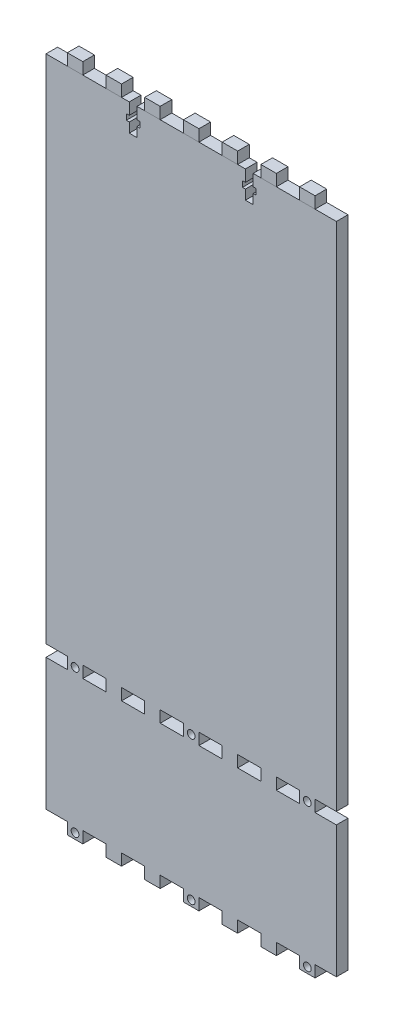
SolidWorks part; units mm, degrees
ref_plane "Plan de face" through (0, 0, 0) normal (0, 0, 1) x (1, 0, 0)
ref_plane "Plan de dessus" through (0, 0, 0) normal (0, 1, 0) x (1, 0, 0)
ref_plane "Plan de droite" through (0, 0, 0) normal (1, 0, 0) x (0, 0, -1)
sketch "Esquisse1" plane through (0, 0, 0) normal (0, 0, 1) x (1, 0, 0)
  line L0 (-166.0227, 1.3653) -> (-16.0227, 1.3653)
  line L1 (-166.0227, 75.3653) -> (-16.0227, 75.3653)
  line L2 (-166.0227, 75.3653) -> (-166.0227, 7.3653)
  line L3 (-166.0227, 7.3653) -> (-16.0227, 7.3653)
  line L4 (-16.0227, 75.3653) -> (-16.0227, 7.3653)
  line L5 (-166.0227, 7.3653) -> (-155.0227, 7.3653)
  line L6 (-166.0227, 7.3653) -> (-166.0227, 1.3653)
  line L7 (-166.0227, 1.3653) -> (-155.0227, 1.3653)
  line L8 (-155.0227, 7.3653) -> (-155.0227, 1.3653)
  line L9 (-155.0227, 1.3653) -> (-147.0227, 1.3653)
  line L10 (-155.0227, 1.3653) -> (-155.0227, 7.3653)
  line L11 (-155.0227, 7.3653) -> (-147.0227, 7.3653)
  line L12 (-147.0227, 1.3653) -> (-147.0227, 7.3653)
  line L13 (-127.0227, 1.3653) -> (-127.0227, 7.3653)
  line L14 (-135.0227, 1.3653) -> (-127.0227, 1.3653)
  line L15 (-135.0227, 7.3653) -> (-135.0227, 1.3653)
  line L16 (-146.0227, 1.3653) -> (-135.0227, 1.3653)
  line L17 (-166.0227, 41.3653) -> (-16.0227, 41.3653) construction
  line L18 (-107.0227, 1.3653) -> (-107.0227, 7.3653)
  line L19 (-115.0227, 1.3653) -> (-107.0227, 1.3653)
  line L20 (-115.0227, 7.3653) -> (-115.0227, 1.3653)
  line L21 (-126.0227, 1.3653) -> (-115.0227, 1.3653)
  line L22 (-46.0227, 81.3653) -> (-35.0227, 81.3653)
  line L23 (-87.0227, 1.3653) -> (-87.0227, 7.3653)
  line L24 (-95.0227, 1.3653) -> (-87.0227, 1.3653)
  line L25 (-95.0227, 7.3653) -> (-95.0227, 1.3653)
  line L26 (-106.0227, 1.3653) -> (-95.0227, 1.3653)
  line L27 (-35.0227, 75.3653) -> (-35.0227, 81.3653)
  line L28 (-67.0227, 1.3653) -> (-67.0227, 7.3653)
  line L29 (-75.0227, 1.3653) -> (-67.0227, 1.3653)
  line L30 (-75.0227, 7.3653) -> (-75.0227, 1.3653)
  line L31 (-86.0227, 1.3653) -> (-75.0227, 1.3653)
  line L32 (-35.0227, 81.3653) -> (-27.0227, 81.3653)
  line L33 (-47.0227, 1.3653) -> (-47.0227, 7.3653)
  line L34 (-55.0227, 1.3653) -> (-47.0227, 1.3653)
  line L35 (-55.0227, 7.3653) -> (-55.0227, 1.3653)
  line L36 (-66.0227, 1.3653) -> (-55.0227, 1.3653)
  line L37 (-27.0227, 81.3653) -> (-27.0227, 75.3653)
  line L38 (-27.0227, 1.3653) -> (-27.0227, 7.3653)
  line L39 (-35.0227, 1.3653) -> (-27.0227, 1.3653)
  line L40 (-35.0227, 7.3653) -> (-35.0227, 1.3653)
  line L41 (-46.0227, 1.3653) -> (-35.0227, 1.3653)
  line L42 (-66.0227, 81.3653) -> (-55.0227, 81.3653)
  line L43 (-55.0227, 75.3653) -> (-55.0227, 81.3653)
  line L44 (-55.0227, 81.3653) -> (-47.0227, 81.3653)
  line L45 (-47.0227, 81.3653) -> (-47.0227, 75.3653)
  line L46 (-86.0227, 81.3653) -> (-75.0227, 81.3653)
  line L47 (-75.0227, 75.3653) -> (-75.0227, 81.3653)
  line L48 (-75.0227, 81.3653) -> (-67.0227, 81.3653)
  line L49 (-67.0227, 81.3653) -> (-67.0227, 75.3653)
  line L50 (-106.0227, 81.3653) -> (-95.0227, 81.3653)
  line L51 (-95.0227, 75.3653) -> (-95.0227, 81.3653)
  line L52 (-95.0227, 81.3653) -> (-87.0227, 81.3653)
  line L53 (-87.0227, 81.3653) -> (-87.0227, 75.3653)
  line L54 (-126.0227, 81.3653) -> (-115.0227, 81.3653)
  line L55 (-115.0227, 75.3653) -> (-115.0227, 81.3653)
  line L56 (-115.0227, 81.3653) -> (-107.0227, 81.3653)
  line L57 (-107.0227, 81.3653) -> (-107.0227, 75.3653)
  line L58 (-146.0227, 81.3653) -> (-135.0227, 81.3653)
  line L59 (-135.0227, 75.3653) -> (-135.0227, 81.3653)
  line L60 (-135.0227, 81.3653) -> (-127.0227, 81.3653)
  line L61 (-127.0227, 81.3653) -> (-127.0227, 75.3653)
  line L62 (-147.0227, 81.3653) -> (-147.0227, 75.3653)
  line L63 (-155.0227, 75.3653) -> (-147.0227, 75.3653)
  line L64 (-155.0227, 81.3653) -> (-155.0227, 75.3653)
  line L65 (-155.0227, 81.3653) -> (-147.0227, 81.3653)
  line L66 (-155.0227, 75.3653) -> (-155.0227, 81.3653)
  line L67 (-166.0227, 81.3653) -> (-155.0227, 81.3653)
  line L68 (-166.0227, 75.3653) -> (-166.0227, 81.3653)
  line L69 (-166.0227, 75.3653) -> (-155.0227, 75.3653)
  line L70 (-166.0227, 75.3653) -> (-16.0227, 75.3653)
  line L71 (-166.0227, 81.3653) -> (-16.0227, 81.3653)
  line L72 (-16.0227, 81.3653) -> (-16.0227, 1.3653)
  dimension "D1" = 68
  dimension "D2" = 150
  dimension "D3" = 6
  dimension "D4" = 11
  dimension "D5" = 8
extrude "Boss.-Extru.1" add sketch "Esquisse1" along normal blind 6 contours L65 L64 L1 L62 | L61 L60 L59 L1 | L57 L56 L55 L1 | L53 L52 L51 L1 | L49 L48 L47 L1 | L45 L44 L43 L1 | L37 L32 L27 L1 | L3 L40 L0 L38 | L3 L35 L0 L33 | L3 L30 L0 L28 | L3 L25 L0 L23 | L3 L20 L0 L18 | L3 L15 L0 L13 | L0 L12 L3 L8 | L17 L2 L3 L72 | L2 L17 L4 L1
sketch "Esquisse2" plane through (0, 0, 6) normal (0, 0, 1) x (1, 0, 0)
  line L0 (-16.0227, 81.3653) -> (-166.0227, 81.3653)
  line L1 (-16.0227, 81.3653) -> (-16.0227, 345.3653)
  line L2 (-16.0227, 345.3653) -> (-166.0227, 345.3653)
  line L3 (-166.0227, 81.3653) -> (-166.0227, 345.3653)
  line L4 (-135.0227, 81.3653) -> (-127.0227, 81.3653) construction
  line L5 (-166.0227, 75.3653) -> (-166.0227, 7.3653) construction
  dimension "D1" = 264
  dimension "D2" = 150
extrude "Boss.-Extru.2" add sketch "Esquisse2" against normal blind 6
sketch "Esquisse3" plane through (0, 0, 6) normal (0, 0, 1) x (1, 0, 0)
  line L0 (-155.0227, 345.3653) -> (-147.0227, 345.3653)
  line L1 (-155.0227, 345.3653) -> (-155.0227, 351.3653)
  line L2 (-155.0227, 351.3653) -> (-147.0227, 351.3653)
  line L3 (-147.0227, 345.3653) -> (-147.0227, 351.3653)
  line L4 (-135.0227, 345.3653) -> (-127.0227, 345.3653)
  line L5 (-135.0227, 345.3653) -> (-135.0227, 351.3653)
  line L6 (-135.0227, 351.3653) -> (-127.0227, 351.3653)
  line L7 (-127.0227, 345.3653) -> (-127.0227, 351.3653)
  line L8 (-115.0598, 345.3653) -> (-107.0598, 345.3653)
  line L9 (-115.0598, 345.3653) -> (-115.0598, 351.3653)
  line L10 (-115.0598, 351.3653) -> (-107.0598, 351.3653)
  line L11 (-107.0598, 345.3653) -> (-107.0598, 351.3653)
  line L12 (-95.0227, 345.3653) -> (-87.0227, 345.3653)
  line L13 (-95.0227, 345.3653) -> (-95.0227, 351.3653)
  line L14 (-95.0227, 351.3653) -> (-87.0227, 351.3653)
  line L15 (-87.0227, 345.3653) -> (-87.0227, 351.3653)
  line L16 (-75.0227, 345.3653) -> (-67.0227, 345.3653)
  line L17 (-75.0227, 345.3653) -> (-75.0227, 351.3653)
  line L18 (-75.0227, 351.3653) -> (-67.0227, 351.3653)
  line L19 (-67.0227, 345.3653) -> (-67.0227, 351.3653)
  line L20 (-55.0227, 345.3653) -> (-47.0227, 345.3653)
  line L21 (-55.0227, 345.3653) -> (-55.0227, 351.3653)
  line L22 (-55.0227, 351.3653) -> (-47.0227, 351.3653)
  line L23 (-47.0227, 345.3653) -> (-47.0227, 351.3653)
  line L24 (-35.0227, 345.3653) -> (-27.0227, 345.3653)
  line L25 (-35.0227, 345.3653) -> (-35.0227, 351.3653)
  line L26 (-35.0227, 351.3653) -> (-27.0227, 351.3653)
  line L27 (-27.0227, 345.3653) -> (-27.0227, 351.3653)
  line L28 (-16.0227, 345.3653) -> (-166.0227, 345.3653) construction
  point P28 (-91.0227, 345.3653)
  point P29 (-91.0227, 345.3653)
  dimension "D1" = 8
  dimension "D2" = 12
  dimension "D3" = 11.9629
  dimension "D4" = 12.0371
  dimension "D5" = 12
  dimension "D6" = 12
  dimension "D7" = 12
  dimension "D8" = 6
extrude "Boss.-Extru.3" add sketch "Esquisse3" against normal blind 6 separate body
sketch "Esquisse4" plane through (0, 0, 6) normal (0, 0, 1) x (1, 0, 0)
  line L0 (-35.0227, 75.3653) -> (-35.0227, 81.3653) construction
  line L1 (-47.0227, 81.3653) -> (-35.0227, 81.3653) construction
  line L2 (-87.0227, 81.3653) -> (-87.0227, 75.3653) construction
  line L3 (-147.0227, 81.3653) -> (-147.0227, 75.3653) construction
  circle A0 centre (-31.0227, 78.3653) radius 2
  circle A1 centre (-151.0227, 78.3653) radius 2
  circle A2 centre (-91.0227, 78.3653) radius 2
  dimension "D1" = 4
  dimension "D2" = 4
  dimension "D3" = 3
  dimension "D4" = 4
  dimension "D5" = 4
extrude "Enlèv. mat.-Extru.1" cut sketch "Esquisse4" against normal through all
sketch "Esquisse5" plane through (0, 0, 6) normal (0, 0, 1) x (1, 0, 0)
  line L0 (-155.0227, 1.3653) -> (-147.0227, 1.3653) construction
  line L2 (-155.0227, 7.3653) -> (-155.0227, 1.3653) construction
  line L3 (-95.0227, 7.3653) -> (-95.0227, 1.3653) construction
  line L4 (-35.0227, 7.3653) -> (-35.0227, 1.3653) construction
  line L5 (-95.0227, 1.3653) -> (-87.0227, 1.3653) construction
  line L6 (-35.0227, 1.3653) -> (-27.0227, 1.3653) construction
  circle A0 centre (-151.0227, 4.3653) radius 2
  circle A1 centre (-91.0227, 4.3653) radius 2
  circle A2 centre (-31.0227, 4.3653) radius 2
  point P10 (-155.0227, 4.7381)
  dimension "D1" = 3
  dimension "D4" = 4
  dimension "D2" = 4
  dimension "D3" = 4
  dimension "D5" = 4
  dimension "D6" = 3
  dimension "D7" = 3
extrude "Enlèv. mat.-Extru.2" cut sketch "Esquisse5" against normal through all
sketch "Esquisse6" plane through (0, 0, 6) normal (0, 0, 1) x (1, 0, 0)
  line L0 (-119.0227, 331.3653) -> (-123.0227, 331.3653)
  line L1 (-119.0227, 331.3653) -> (-119.0227, 345.3653)
  line L2 (-119.0227, 345.3653) -> (-123.0227, 345.3653)
  line L3 (-123.0227, 331.3653) -> (-123.0227, 345.3653)
  line L4 (-117.5227, 336.3653) -> (-124.5227, 336.3653)
  line L5 (-117.5227, 336.3653) -> (-117.5227, 339.3653)
  line L6 (-117.5227, 339.3653) -> (-124.5227, 339.3653)
  line L7 (-124.5227, 336.3653) -> (-124.5227, 339.3653)
  line L8 (-16.0227, 345.3653) -> (-166.0227, 345.3653) construction
  line L9 (-127.0227, 345.3653) -> (-127.0227, 351.3653) construction
  line L10 (-59.0227, 331.3653) -> (-63.0227, 331.3653)
  line L11 (-59.0227, 331.3653) -> (-59.0227, 345.3653)
  line L12 (-59.0227, 345.3653) -> (-63.0227, 345.3653)
  line L13 (-63.0227, 331.3653) -> (-63.0227, 345.3653)
  line L14 (-57.5227, 336.3653) -> (-64.5227, 336.3653)
  line L15 (-57.5227, 336.3653) -> (-57.5227, 339.3653)
  line L16 (-57.5227, 339.3653) -> (-64.5227, 339.3653)
  line L17 (-64.5227, 336.3653) -> (-64.5227, 339.3653)
  line L18 (-67.0227, 345.3653) -> (-67.0227, 351.3653) construction
  dimension "D1" = 4
  dimension "D2" = 14
  dimension "D3" = 3
  dimension "D4" = 7
  dimension "D5" = 1.5
  dimension "D6" = 6
  dimension "D7" = 4
  dimension "D8" = 4
  dimension "D9" = 14
  dimension "D10" = 3
  dimension "D11" = 7
  dimension "D12" = 1.5
  dimension "D13" = 5
  dimension "D14" = 4
extrude "Enlèv. mat.-Extru.3" cut sketch "Esquisse6" against normal through all contours L13 L12 L11 L10 | L17 L16 L15 L14 | L3 L2 L1 L0 | L6 L7 L4 L5
